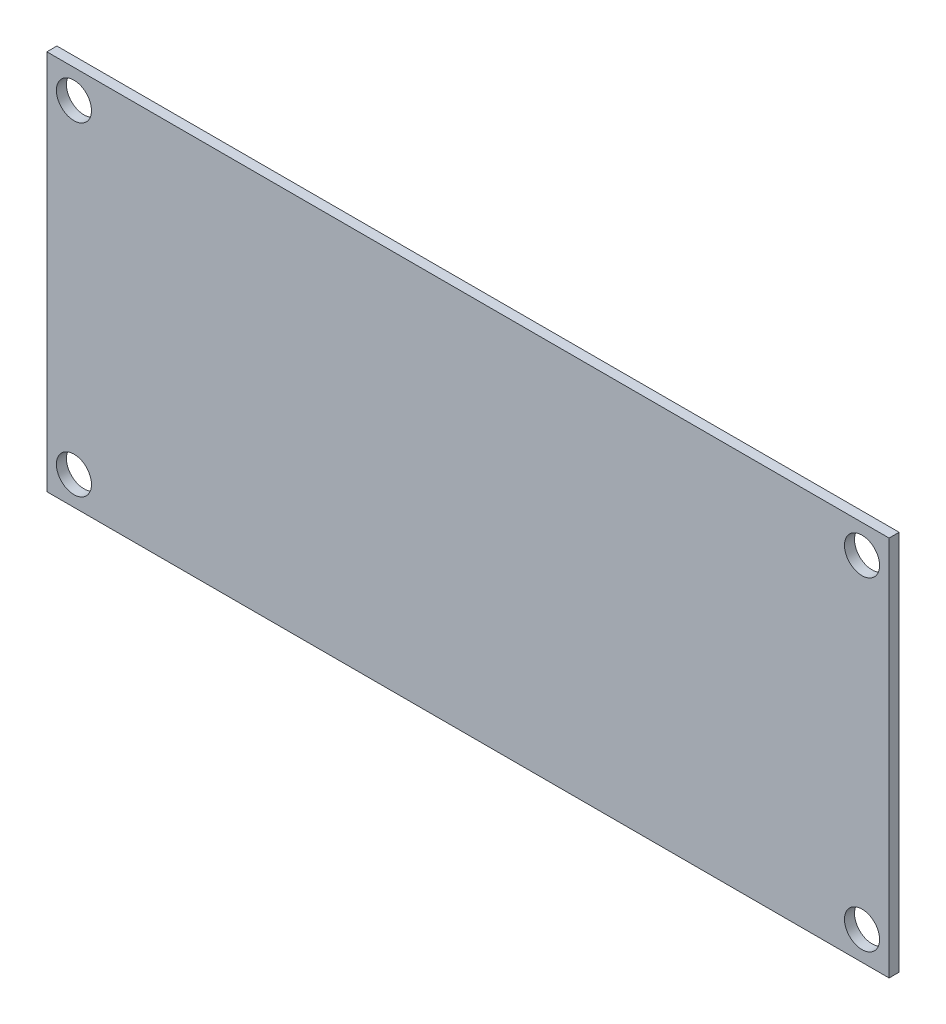
SolidWorks part; units mm, degrees
ref_plane "Plano frontal" through (0, 0, 0) normal (0, 0, 1) x (1, 0, 0)
ref_plane "Plano superior" through (0, 0, 0) normal (0, 1, 0) x (1, 0, 0)
ref_plane "Plano direito" through (0, 0, 0) normal (1, 0, 0) x (0, 0, -1)
sketch "Esboço1" plane through (0, 0, 0) normal (0, 0, 1) x (1, 0, 0)
  line L1 (-39.3, -16.15) -> (39.3, -16.15) construction
  line L2 (-39.3, -16.15) -> (-39.3, 16.15) construction
  line L3 (-39.3, 16.15) -> (39.3, 16.15) construction
  line L4 (39.3, -16.15) -> (39.3, 16.15) construction
  line L5 (-39.3, -16.15) -> (39.3, 16.15) construction
  line L6 (-39.3, 16.15) -> (39.3, -16.15) construction
  line L7 (-42, -19) -> (42, -19)
  line L8 (-42, -19) -> (-42, 19)
  line L9 (-42, 19) -> (42, 19)
  line L10 (42, -19) -> (42, 19)
  line L11 (-42, -19) -> (42, 19) construction
  line L12 (-42, 19) -> (42, -19) construction
  circle A0 centre (-39.3, 16.15) radius 1.75
  circle A1 centre (39.3, 16.15) radius 1.75
  circle A2 centre (-39.3, -16.15) radius 1.75
  circle A3 centre (39.3, -16.15) radius 1.75
  point P0 (0, 0)
  point P5 (0, 0)
  dimension "D3" = 84
  dimension "D5" = 3.5
  dimension "D1" = 78.6
  dimension "D2" = 32.3
  dimension "D4" = 38
extrude "Ressalto-extrusão1" add sketch "Esboço1" along normal blind 1
